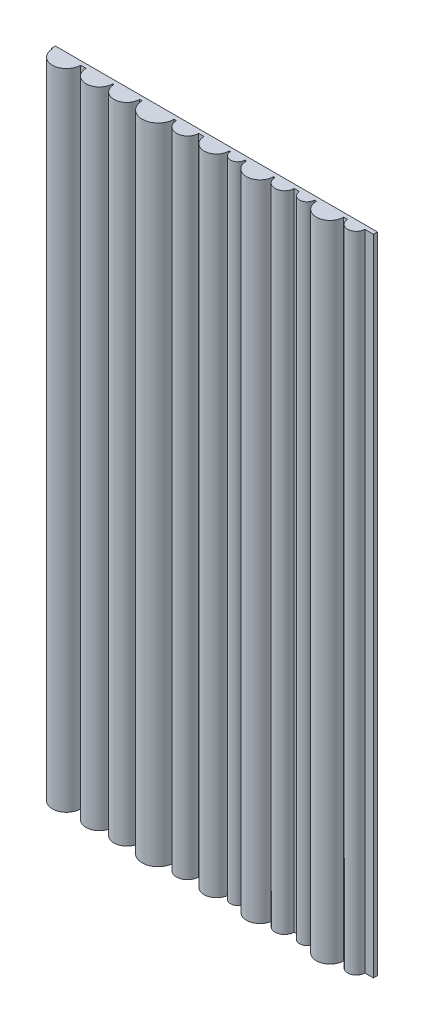
SolidWorks part; units mm, degrees
ref_plane "前视基准面" through (0, 0, 0) normal (0, 0, 1) x (1, 0, 0)
ref_plane "上视基准面" through (0, 0, 0) normal (0, 1, 0) x (1, 0, 0)
ref_plane "右视基准面" through (0, 0, 0) normal (1, 0, 0) x (0, 0, -1)
sketch "草图1" plane through (0, 0, 0) normal (0, 0, 1) x (1, 0, 0)
  line L1 (0, 0) -> (8, 0)
  line L2 (0, 0) -> (0, 16)
  line L3 (0, 16) -> (8, 16)
  line L4 (8, 0) -> (8, 16)
extrude "凸台-拉伸1" add sketch "草图1" along normal blind 0.1
sketch "草图2" plane through (0, 0, 0) normal (0, -1, 0) x (1, 0, 0)
  line L0 (0, 0.1) -> (8, 0.1) construction
  circle A0 centre (0.3751, 0.1) radius 0.3511
  circle A2 centre (1.8749, 0.1) radius 0.3201
  circle A4 centre (3.3838, 0.1) radius 0.2753
  circle A5 centre (4.1057, 0.1) radius 0.3118
  circle A6 centre (5.1835, 0.1) radius 0.337
  circle A8 centre (5.7936, 0.1) radius 0.2373
  circle A9 centre (6.346, 0.1) radius 0.183
  circle A11 centre (7.5729, 0.1) radius 0.213
  circle A12 centre (1.1923, 0.1) radius 0.3325
  circle A13 centre (2.6517, 0.1) radius 0.397
  circle A15 centre (4.6276, 0.1) radius 0.1796
  circle A16 centre (6.9222, 0.1) radius 0.3403
extrude "凸台-拉伸2" add sketch "草图2" against normal up to surface (16 mm away) up to face at (4, 16, 0.05)
sketch "草图3" plane through (0, 0, 0) normal (0, -1, 0) x (1, 0, 0)
  line L1 (0, 0) -> (8, 0)
  line L2 (0, 0) -> (0, -0.452)
  line L3 (0, -0.452) -> (8, -0.452)
  line L4 (8, 0) -> (8, -0.452)
extrude "切除-拉伸1" cut sketch "草图3" against normal up to surface (16 mm away) up to face at (4.1561, 16, 0.0731)
